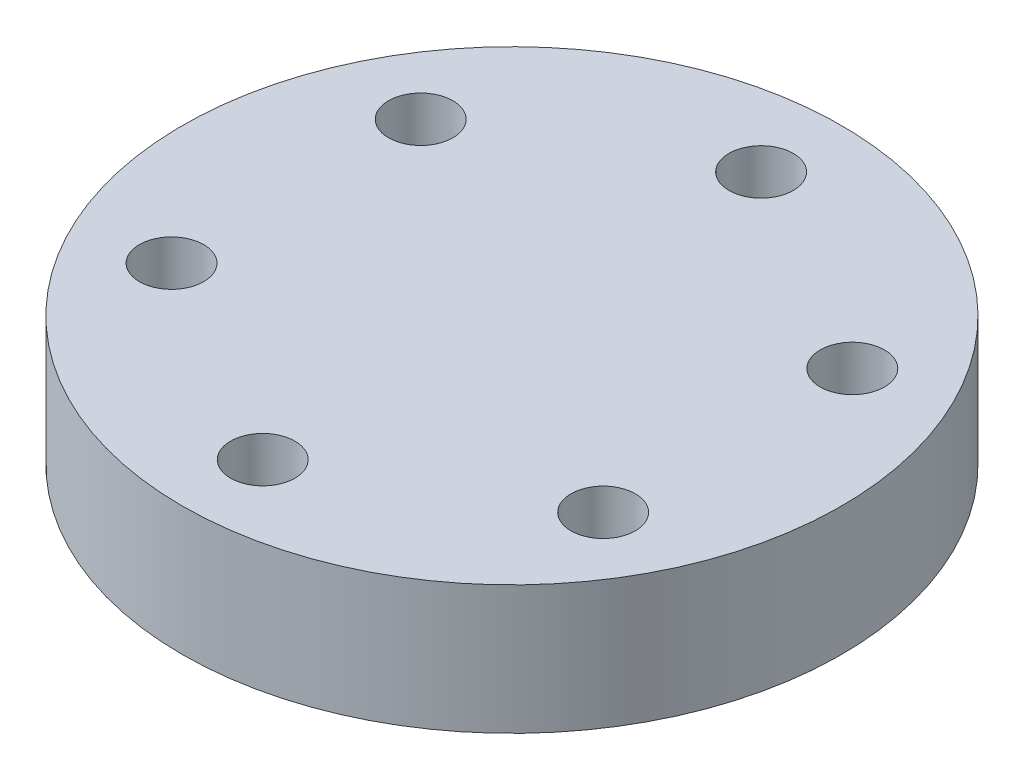
SolidWorks part; units mm, degrees
ref_plane "前基準面" through (0, 0, 0) normal (0, 0, 1) x (1, 0, 0)
ref_plane "上基準面" through (0, 0, 0) normal (0, 1, 0) x (1, 0, 0)
ref_plane "右基準面" through (0, 0, 0) normal (1, 0, 0) x (0, 0, -1)
sketch "草圖1" plane through (0, 0, 0) normal (0, 1, 0) x (1, 0, 0)
  circle A0 centre (0, 0) radius 20.5
  dimension "D1" = 41
extrude "填料-伸長1" add sketch "草圖1" along normal blind 8
sketch "草圖2" plane through (0, 8, 0) normal (0, 1, 0) x (1, 0, 0)
  circle A0 centre (0, 15.5) radius 2
  dimension "D1" = 4
  dimension "D2" = 15.5
extrude "除料-伸長1" cut sketch "草圖2" against normal up to next
pattern_circular "環狀複製排列1" count 6 over 360 about axis through (0, 0, 0) along (0, 1, 0) of "除料-伸長1"
